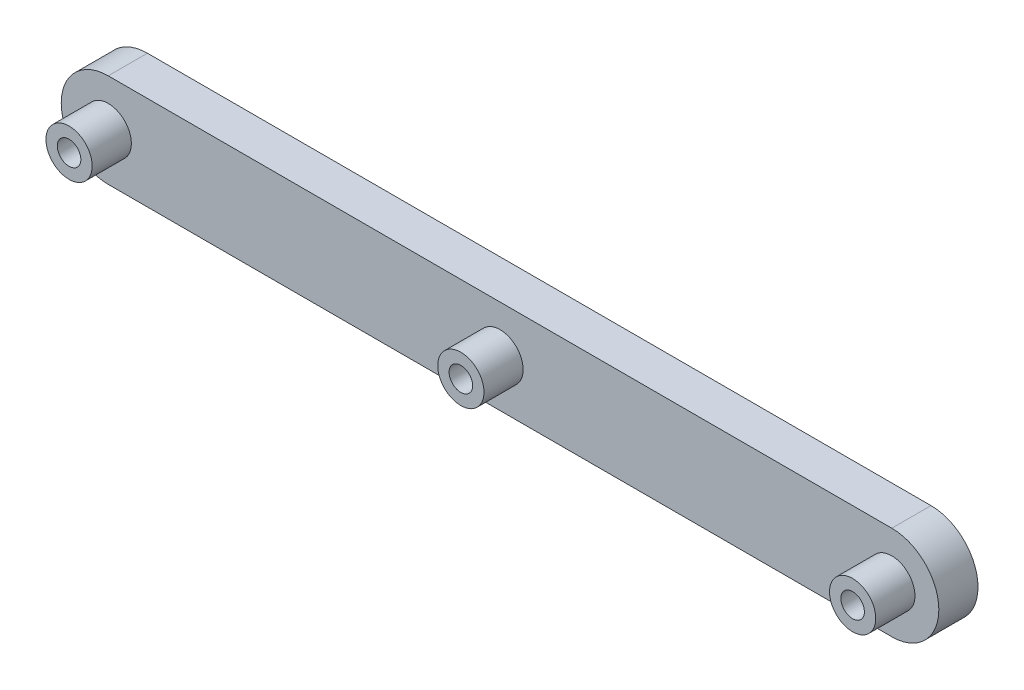
SolidWorks part; units mm, degrees
ref_plane "Front Plane" through (0, 0, 0) normal (0, 0, 1) x (1, 0, 0)
ref_plane "Top Plane" through (0, 0, 0) normal (0, 1, 0) x (1, 0, 0)
ref_plane "Right Plane" through (0, 0, 0) normal (1, 0, 0) x (0, 0, -1)
sketch "Sketch1" plane through (0, 0, 0) normal (0, 0, 1) x (1, 0, 0)
  line L0 (-50, 0) -> (50, 0) construction
  line L1 (-50, 6) -> (50, 6)
  line L2 (-50, -6) -> (50, -6)
  arc A0 (-50, 6) -> (-50, -6) centre (-50, 0) ccw
  arc A1 (50, -6) -> (50, 6) centre (50, 0) ccw
  circle A2 centre (-50, 0) radius 1.5
  circle A3 centre (50, 0) radius 1.5
  circle A4 centre (0, 0) radius 1.5
  point P2 (0, 0)
  dimension "D2" = 6
  dimension "D3" = 3
  dimension "D1" = 100
extrude "Boss-Extrude1" add sketch "Sketch1" along normal blind 5
sketch "Sketch2" plane through (0, 0, 5) normal (0, 0, 1) x (1, 0, 0)
  circle A0 centre (-50, 0) radius 2.95
  circle A1 centre (0, 0) radius 2.95
  circle A2 centre (50, 0) radius 1.5 construction
  circle A3 centre (-50, 0) radius 1.5 construction
  circle A4 centre (0, 0) radius 1.5 construction
  circle A6 centre (-50, 0) radius 1.5
  circle A7 centre (0, 0) radius 1.5
  circle A8 centre (50, 0) radius 1.5
  circle A9 centre (50, 0) radius 2.95
  dimension "D1" = 5.9
extrude "Boss-Extrude2" add sketch "Sketch2" along normal blind 5
sketch "Sketch4" plane through (0, 0, 0) normal (0, 0, -1) x (-1, 0, 0)
  circle A0 centre (-50, 0) radius 2.5
  circle A1 centre (0, 0) radius 2.5
  circle A2 centre (50, 0) radius 2.5
  dimension "D1" = 5
extrude "Cut-Extrude1" cut sketch "Sketch4" against normal blind 2
